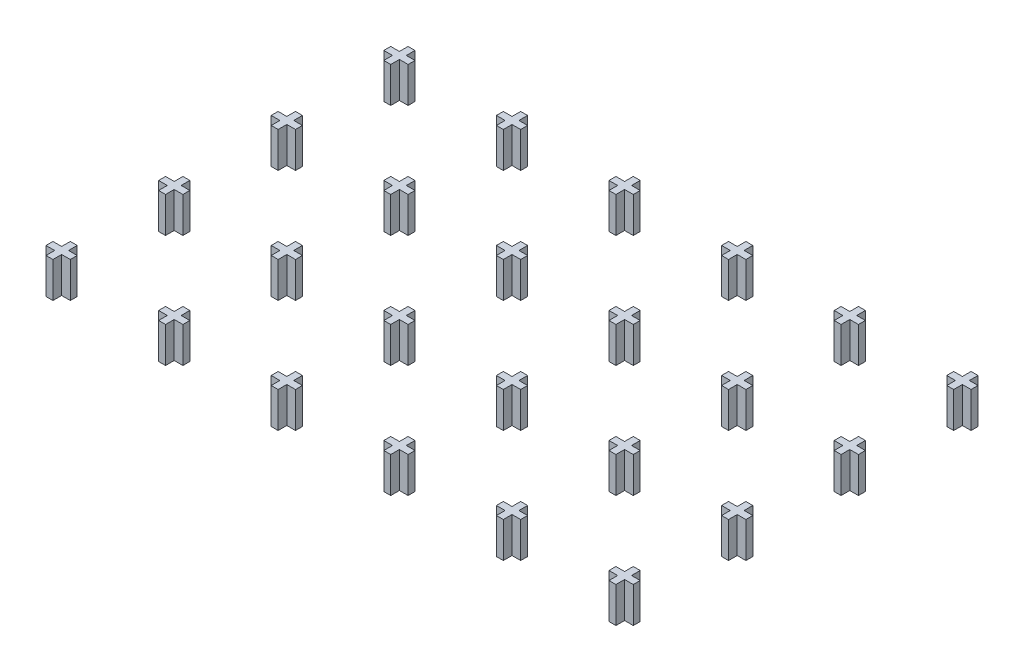
SolidWorks part; units mm, degrees
ref_plane "Front Plane" through (0, 0, 0) normal (0, 0, 1) x (1, 0, 0)
ref_plane "Top Plane" through (0, 0, 0) normal (0, 1, 0) x (1, 0, 0)
ref_plane "Right Plane" through (0, 0, 0) normal (1, 0, 0) x (0, 0, -1)
sketch "Sketch1" plane through (0, 0, 0) normal (0, 1, 0) x (1, 0, 0)
  line L0 (-32.7876, 10.5773) -> (-51.7876, 10.5773) construction
  line L1 (-51.7876, 10.5773) -> (-70.7876, 10.5773) construction
  line L2 (-51.7876, 10.5773) -> (-51.7876, 29.5773) construction
  line L3 (-51.7876, 29.5773) -> (-70.7876, 29.5773) construction
  line L4 (-70.7876, 10.5773) -> (-70.7876, 29.5773) construction
  line L5 (-51.7876, 10.5773) -> (-70.7876, 29.5773) construction
  line L6 (-51.7876, 29.5773) -> (-70.7876, 10.5773) construction
  line L7 (-32.7876, 10.5773) -> (-32.7876, 29.5773) construction
  line L8 (-32.7876, 29.5773) -> (-51.7876, 29.5773) construction
  line L9 (-51.7876, 10.5773) -> (-51.7876, 29.5773) construction
  line L10 (-32.7876, 10.5773) -> (-51.7876, 29.5773) construction
  line L11 (-32.7876, 29.5773) -> (-51.7876, 10.5773) construction
  line L12 (-13.7876, 10.5773) -> (-32.7876, 10.5773) construction
  line L13 (-13.7876, 10.5773) -> (-13.7876, 29.5773) construction
  line L14 (-13.7876, 29.5773) -> (-32.7876, 29.5773) construction
  line L15 (-32.7876, 10.5773) -> (-32.7876, 29.5773) construction
  line L16 (-13.7876, 10.5773) -> (-32.7876, 29.5773) construction
  line L17 (-13.7876, 29.5773) -> (-32.7876, 10.5773) construction
  line L18 (-32.7876, -8.4227) -> (-51.7876, -8.4227) construction
  line L19 (-51.7876, -8.4227) -> (-70.7876, -8.4227) construction
  line L20 (-51.7876, -8.4227) -> (-51.7876, 10.5773) construction
  line L21 (-51.7876, 10.5773) -> (-70.7876, 10.5773) construction
  line L22 (-70.7876, -8.4227) -> (-70.7876, 10.5773) construction
  line L23 (-51.7876, -8.4227) -> (-70.7876, 10.5773) construction
  line L24 (-51.7876, 10.5773) -> (-70.7876, -8.4227) construction
  line L25 (-32.7876, -8.4227) -> (-32.7876, 10.5773) construction
  line L26 (-32.7876, 10.5773) -> (-51.7876, 10.5773) construction
  line L27 (-51.7876, -8.4227) -> (-51.7876, 10.5773) construction
  line L28 (-32.7876, -8.4227) -> (-51.7876, 10.5773) construction
  line L29 (-32.7876, 10.5773) -> (-51.7876, -8.4227) construction
  line L30 (-13.7876, -8.4227) -> (-32.7876, -8.4227) construction
  line L31 (-13.7876, -8.4227) -> (-13.7876, 10.5773) construction
  line L32 (-13.7876, 10.5773) -> (-32.7876, 10.5773) construction
  line L33 (-32.7876, -8.4227) -> (-32.7876, 10.5773) construction
  line L34 (-13.7876, -8.4227) -> (-32.7876, 10.5773) construction
  line L35 (-13.7876, 10.5773) -> (-32.7876, -8.4227) construction
  line L36 (-32.7876, -27.4227) -> (-51.7876, -27.4227) construction
  line L37 (-51.7876, -27.4227) -> (-70.7876, -27.4227) construction
  line L38 (-51.7876, -27.4227) -> (-51.7876, -8.4227) construction
  line L39 (-51.7876, -8.4227) -> (-70.7876, -8.4227) construction
  line L40 (-70.7876, -27.4227) -> (-70.7876, -8.4227) construction
  line L41 (-51.7876, -27.4227) -> (-70.7876, -8.4227) construction
  line L42 (-51.7876, -8.4227) -> (-70.7876, -27.4227) construction
  line L43 (-32.7876, -27.4227) -> (-32.7876, -8.4227) construction
  line L44 (-32.7876, -8.4227) -> (-51.7876, -8.4227) construction
  line L45 (-51.7876, -27.4227) -> (-51.7876, -8.4227) construction
  line L46 (-32.7876, -27.4227) -> (-51.7876, -8.4227) construction
  line L47 (-32.7876, -8.4227) -> (-51.7876, -27.4227) construction
  line L48 (-13.7876, -27.4227) -> (-32.7876, -27.4227) construction
  line L49 (-13.7876, -27.4227) -> (-13.7876, -8.4227) construction
  line L50 (-13.7876, -8.4227) -> (-32.7876, -8.4227) construction
  line L51 (-32.7876, -27.4227) -> (-32.7876, -8.4227) construction
  line L52 (-13.7876, -27.4227) -> (-32.7876, -8.4227) construction
  line L53 (-13.7876, -8.4227) -> (-32.7876, -27.4227) construction
  line L54 (24.2124, 10.5773) -> (5.2124, 10.5773) construction
  line L55 (5.2124, 10.5773) -> (-13.7876, 10.5773) construction
  line L56 (5.2124, 10.5773) -> (5.2124, 29.5773) construction
  line L57 (5.2124, 29.5773) -> (-13.7876, 29.5773) construction
  line L58 (-13.7876, 10.5773) -> (-13.7876, 29.5773) construction
  line L59 (5.2124, 10.5773) -> (-13.7876, 29.5773) construction
  line L60 (5.2124, 29.5773) -> (-13.7876, 10.5773) construction
  line L61 (24.2124, 10.5773) -> (24.2124, 29.5773) construction
  line L62 (24.2124, 29.5773) -> (5.2124, 29.5773) construction
  line L63 (5.2124, 10.5773) -> (5.2124, 29.5773) construction
  line L64 (24.2124, 10.5773) -> (5.2124, 29.5773) construction
  line L65 (24.2124, 29.5773) -> (5.2124, 10.5773) construction
  line L66 (43.2124, 10.5773) -> (24.2124, 10.5773) construction
  line L67 (43.2124, 10.5773) -> (43.2124, 29.5773) construction
  line L68 (43.2124, 29.5773) -> (24.2124, 29.5773) construction
  line L69 (24.2124, 10.5773) -> (24.2124, 29.5773) construction
  line L70 (43.2124, 10.5773) -> (24.2124, 29.5773) construction
  line L71 (43.2124, 29.5773) -> (24.2124, 10.5773) construction
  line L72 (24.2124, -8.4227) -> (5.2124, -8.4227) construction
  line L73 (5.2124, -8.4227) -> (-13.7876, -8.4227) construction
  line L74 (5.2124, -8.4227) -> (5.2124, 10.5773) construction
  line L75 (5.2124, 10.5773) -> (-13.7876, 10.5773) construction
  line L76 (-13.7876, -8.4227) -> (-13.7876, 10.5773) construction
  line L77 (5.2124, -8.4227) -> (-13.7876, 10.5773) construction
  line L78 (5.2124, 10.5773) -> (-13.7876, -8.4227) construction
  line L79 (24.2124, -8.4227) -> (24.2124, 10.5773) construction
  line L80 (24.2124, 10.5773) -> (5.2124, 10.5773) construction
  line L81 (5.2124, -8.4227) -> (5.2124, 10.5773) construction
  line L82 (24.2124, -8.4227) -> (5.2124, 10.5773) construction
  line L83 (24.2124, 10.5773) -> (5.2124, -8.4227) construction
  line L84 (43.2124, -8.4227) -> (24.2124, -8.4227) construction
  line L85 (43.2124, -8.4227) -> (43.2124, 10.5773) construction
  line L86 (43.2124, 10.5773) -> (24.2124, 10.5773) construction
  line L87 (24.2124, -8.4227) -> (24.2124, 10.5773) construction
  line L88 (43.2124, -8.4227) -> (24.2124, 10.5773) construction
  line L89 (43.2124, 10.5773) -> (24.2124, -8.4227) construction
  line L90 (24.2124, -27.4227) -> (5.2124, -27.4227) construction
  line L91 (5.2124, -27.4227) -> (-13.7876, -27.4227) construction
  line L92 (5.2124, -27.4227) -> (5.2124, -8.4227) construction
  line L93 (5.2124, -8.4227) -> (-13.7876, -8.4227) construction
  line L94 (-13.7876, -27.4227) -> (-13.7876, -8.4227) construction
  line L95 (5.2124, -27.4227) -> (-13.7876, -8.4227) construction
  line L96 (5.2124, -8.4227) -> (-13.7876, -27.4227) construction
  line L97 (24.2124, -27.4227) -> (24.2124, -8.4227) construction
  line L98 (24.2124, -8.4227) -> (5.2124, -8.4227) construction
  line L99 (5.2124, -27.4227) -> (5.2124, -8.4227) construction
  line L100 (24.2124, -27.4227) -> (5.2124, -8.4227) construction
  line L101 (24.2124, -8.4227) -> (5.2124, -27.4227) construction
  line L102 (43.2124, -27.4227) -> (24.2124, -27.4227) construction
  line L103 (43.2124, -27.4227) -> (43.2124, -8.4227) construction
  line L104 (43.2124, -8.4227) -> (24.2124, -8.4227) construction
  line L105 (24.2124, -27.4227) -> (24.2124, -8.4227) construction
  line L106 (43.2124, -27.4227) -> (24.2124, -8.4227) construction
  line L107 (43.2124, -8.4227) -> (24.2124, -27.4227) construction
  line L108 (-61.8726, 22.1273) -> (-60.7026, 22.1273)
  line L109 (-60.7026, 22.1273) -> (-60.7026, 20.6623)
  line L110 (-60.7026, 20.6623) -> (-59.2376, 20.6623)
  line L111 (-59.2376, 20.6623) -> (-59.2376, 19.4923)
  line L112 (-59.2376, 19.4923) -> (-60.7026, 19.4923)
  line L113 (-60.7026, 19.4923) -> (-60.7026, 18.0273)
  line L114 (-60.7026, 18.0273) -> (-61.8726, 18.0273)
  line L115 (-61.8726, 18.0273) -> (-61.8726, 19.4923)
  line L116 (-61.8726, 19.4923) -> (-63.3376, 19.4923)
  line L117 (-63.3376, 19.4923) -> (-63.3376, 20.6623)
  line L118 (-63.3376, 20.6623) -> (-61.8726, 20.6623)
  line L119 (-61.8726, 20.6623) -> (-61.8726, 22.1273)
  line L120 (-61.8726, 20.6623) -> (-60.7026, 19.4923) construction
  line L121 (-61.8726, 19.4923) -> (-60.7026, 20.6623) construction
  line L122 (-61.8726, 3.1273) -> (-60.7026, 3.1273)
  line L123 (-60.7026, 3.1273) -> (-60.7026, 1.6623)
  line L124 (-60.7026, 1.6623) -> (-59.2376, 1.6623)
  line L125 (-59.2376, 1.6623) -> (-59.2376, 0.4923)
  line L126 (-59.2376, 0.4923) -> (-60.7026, 0.4923)
  line L127 (-60.7026, 0.4923) -> (-60.7026, -0.9727)
  line L128 (-60.7026, -0.9727) -> (-61.8726, -0.9727)
  line L129 (-61.8726, -0.9727) -> (-61.8726, 0.4923)
  line L130 (-61.8726, 0.4923) -> (-63.3376, 0.4923)
  line L131 (-63.3376, 0.4923) -> (-63.3376, 1.6623)
  line L132 (-63.3376, 1.6623) -> (-61.8726, 1.6623)
  line L133 (-61.8726, 1.6623) -> (-61.8726, 3.1273)
  line L134 (-61.8726, 1.6623) -> (-60.7026, 0.4923) construction
  line L135 (-61.8726, 0.4923) -> (-60.7026, 1.6623) construction
  line L136 (-61.8726, -15.8727) -> (-60.7026, -15.8727)
  line L137 (-60.7026, -15.8727) -> (-60.7026, -17.3377)
  line L138 (-60.7026, -17.3377) -> (-59.2376, -17.3377)
  line L139 (-59.2376, -17.3377) -> (-59.2376, -18.5077)
  line L140 (-59.2376, -18.5077) -> (-60.7026, -18.5077)
  line L141 (-60.7026, -18.5077) -> (-60.7026, -19.9727)
  line L142 (-60.7026, -19.9727) -> (-61.8726, -19.9727)
  line L143 (-61.8726, -19.9727) -> (-61.8726, -18.5077)
  line L144 (-61.8726, -18.5077) -> (-63.3376, -18.5077)
  line L145 (-63.3376, -18.5077) -> (-63.3376, -17.3377)
  line L146 (-63.3376, -17.3377) -> (-61.8726, -17.3377)
  line L147 (-61.8726, -17.3377) -> (-61.8726, -15.8727)
  line L148 (-61.8726, -17.3377) -> (-60.7026, -18.5077) construction
  line L149 (-61.8726, -18.5077) -> (-60.7026, -17.3377) construction
  line L150 (-42.8726, -15.8727) -> (-41.7026, -15.8727)
  line L151 (-41.7026, -15.8727) -> (-41.7026, -17.3377)
  line L152 (-41.7026, -17.3377) -> (-40.2376, -17.3377)
  line L153 (-40.2376, -17.3377) -> (-40.2376, -18.5077)
  line L154 (-40.2376, -18.5077) -> (-41.7026, -18.5077)
  line L155 (-41.7026, -18.5077) -> (-41.7026, -19.9727)
  line L156 (-41.7026, -19.9727) -> (-42.8726, -19.9727)
  line L157 (-42.8726, -19.9727) -> (-42.8726, -18.5077)
  line L158 (-42.8726, -18.5077) -> (-44.3376, -18.5077)
  line L159 (-44.3376, -18.5077) -> (-44.3376, -17.3377)
  line L160 (-44.3376, -17.3377) -> (-42.8726, -17.3377)
  line L161 (-42.8726, -17.3377) -> (-42.8726, -15.8727)
  line L162 (-42.8726, -17.3377) -> (-41.7026, -18.5077) construction
  line L163 (-42.8726, -18.5077) -> (-41.7026, -17.3377) construction
  line L164 (-42.8726, 3.1273) -> (-41.7026, 3.1273)
  line L165 (-41.7026, 3.1273) -> (-41.7026, 1.6623)
  line L166 (-41.7026, 1.6623) -> (-40.2376, 1.6623)
  line L167 (-40.2376, 1.6623) -> (-40.2376, 0.4923)
  line L168 (-40.2376, 0.4923) -> (-41.7026, 0.4923)
  line L169 (-41.7026, 0.4923) -> (-41.7026, -0.9727)
  line L170 (-41.7026, -0.9727) -> (-42.8726, -0.9727)
  line L171 (-42.8726, -0.9727) -> (-42.8726, 0.4923)
  line L172 (-42.8726, 0.4923) -> (-44.3376, 0.4923)
  line L173 (-44.3376, 0.4923) -> (-44.3376, 1.6623)
  line L174 (-44.3376, 1.6623) -> (-42.8726, 1.6623)
  line L175 (-42.8726, 1.6623) -> (-42.8726, 3.1273)
  line L176 (-42.8726, 1.6623) -> (-41.7026, 0.4923) construction
  line L177 (-42.8726, 0.4923) -> (-41.7026, 1.6623) construction
  line L178 (-42.8726, 22.1273) -> (-41.7026, 22.1273)
  line L179 (-41.7026, 22.1273) -> (-41.7026, 20.6623)
  line L180 (-41.7026, 20.6623) -> (-40.2376, 20.6623)
  line L181 (-40.2376, 20.6623) -> (-40.2376, 19.4923)
  line L182 (-40.2376, 19.4923) -> (-41.7026, 19.4923)
  line L183 (-41.7026, 19.4923) -> (-41.7026, 18.0273)
  line L184 (-41.7026, 18.0273) -> (-42.8726, 18.0273)
  line L185 (-42.8726, 18.0273) -> (-42.8726, 19.4923)
  line L186 (-42.8726, 19.4923) -> (-44.3376, 19.4923)
  line L187 (-44.3376, 19.4923) -> (-44.3376, 20.6623)
  line L188 (-44.3376, 20.6623) -> (-42.8726, 20.6623)
  line L189 (-42.8726, 20.6623) -> (-42.8726, 22.1273)
  line L190 (-42.8726, 20.6623) -> (-41.7026, 19.4923) construction
  line L191 (-42.8726, 19.4923) -> (-41.7026, 20.6623) construction
  line L192 (-23.8726, 22.1273) -> (-22.7026, 22.1273)
  line L193 (-22.7026, 22.1273) -> (-22.7026, 20.6623)
  line L194 (-22.7026, 20.6623) -> (-21.2376, 20.6623)
  line L195 (-21.2376, 20.6623) -> (-21.2376, 19.4923)
  line L196 (-21.2376, 19.4923) -> (-22.7026, 19.4923)
  line L197 (-22.7026, 19.4923) -> (-22.7026, 18.0273)
  line L198 (-22.7026, 18.0273) -> (-23.8726, 18.0273)
  line L199 (-23.8726, 18.0273) -> (-23.8726, 19.4923)
  line L200 (-23.8726, 19.4923) -> (-25.3376, 19.4923)
  line L201 (-25.3376, 19.4923) -> (-25.3376, 20.6623)
  line L202 (-25.3376, 20.6623) -> (-23.8726, 20.6623)
  line L203 (-23.8726, 20.6623) -> (-23.8726, 22.1273)
  line L204 (-23.8726, 20.6623) -> (-22.7026, 19.4923) construction
  line L205 (-23.8726, 19.4923) -> (-22.7026, 20.6623) construction
  line L206 (-23.8726, 3.1273) -> (-22.7026, 3.1273)
  line L207 (-22.7026, 3.1273) -> (-22.7026, 1.6623)
  line L208 (-22.7026, 1.6623) -> (-21.2376, 1.6623)
  line L209 (-21.2376, 1.6623) -> (-21.2376, 0.4923)
  line L210 (-21.2376, 0.4923) -> (-22.7026, 0.4923)
  line L211 (-22.7026, 0.4923) -> (-22.7026, -0.9727)
  line L212 (-22.7026, -0.9727) -> (-23.8726, -0.9727)
  line L213 (-23.8726, -0.9727) -> (-23.8726, 0.4923)
  line L214 (-23.8726, 0.4923) -> (-25.3376, 0.4923)
  line L215 (-25.3376, 0.4923) -> (-25.3376, 1.6623)
  line L216 (-25.3376, 1.6623) -> (-23.8726, 1.6623)
  line L217 (-23.8726, 1.6623) -> (-23.8726, 3.1273)
  line L218 (-23.8726, 1.6623) -> (-22.7026, 0.4923) construction
  line L219 (-23.8726, 0.4923) -> (-22.7026, 1.6623) construction
  line L220 (-23.8726, -15.8727) -> (-22.7026, -15.8727)
  line L221 (-22.7026, -15.8727) -> (-22.7026, -17.3377)
  line L222 (-22.7026, -17.3377) -> (-21.2376, -17.3377)
  line L223 (-21.2376, -17.3377) -> (-21.2376, -18.5077)
  line L224 (-21.2376, -18.5077) -> (-22.7026, -18.5077)
  line L225 (-22.7026, -18.5077) -> (-22.7026, -19.9727)
  line L226 (-22.7026, -19.9727) -> (-23.8726, -19.9727)
  line L227 (-23.8726, -19.9727) -> (-23.8726, -18.5077)
  line L228 (-23.8726, -18.5077) -> (-25.3376, -18.5077)
  line L229 (-25.3376, -18.5077) -> (-25.3376, -17.3377)
  line L230 (-25.3376, -17.3377) -> (-23.8726, -17.3377)
  line L231 (-23.8726, -17.3377) -> (-23.8726, -15.8727)
  line L232 (-23.8726, -17.3377) -> (-22.7026, -18.5077) construction
  line L233 (-23.8726, -18.5077) -> (-22.7026, -17.3377) construction
  line L234 (-4.8726, -15.8727) -> (-3.7026, -15.8727)
  line L235 (-3.7026, -15.8727) -> (-3.7026, -17.3377)
  line L236 (-3.7026, -17.3377) -> (-2.2376, -17.3377)
  line L237 (-2.2376, -17.3377) -> (-2.2376, -18.5077)
  line L238 (-2.2376, -18.5077) -> (-3.7026, -18.5077)
  line L239 (-3.7026, -18.5077) -> (-3.7026, -19.9727)
  line L240 (-3.7026, -19.9727) -> (-4.8726, -19.9727)
  line L241 (-4.8726, -19.9727) -> (-4.8726, -18.5077)
  line L242 (-4.8726, -18.5077) -> (-6.3376, -18.5077)
  line L243 (-6.3376, -18.5077) -> (-6.3376, -17.3377)
  line L244 (-6.3376, -17.3377) -> (-4.8726, -17.3377)
  line L245 (-4.8726, -17.3377) -> (-4.8726, -15.8727)
  line L246 (-4.8726, -17.3377) -> (-3.7026, -18.5077) construction
  line L247 (-4.8726, -18.5077) -> (-3.7026, -17.3377) construction
  line L248 (-4.8726, 3.1273) -> (-3.7026, 3.1273)
  line L249 (-3.7026, 3.1273) -> (-3.7026, 1.6623)
  line L250 (-3.7026, 1.6623) -> (-2.2376, 1.6623)
  line L251 (-2.2376, 1.6623) -> (-2.2376, 0.4923)
  line L252 (-2.2376, 0.4923) -> (-3.7026, 0.4923)
  line L253 (-3.7026, 0.4923) -> (-3.7026, -0.9727)
  line L254 (-3.7026, -0.9727) -> (-4.8726, -0.9727)
  line L255 (-4.8726, -0.9727) -> (-4.8726, 0.4923)
  line L256 (-4.8726, 0.4923) -> (-6.3376, 0.4923)
  line L257 (-6.3376, 0.4923) -> (-6.3376, 1.6623)
  line L258 (-6.3376, 1.6623) -> (-4.8726, 1.6623)
  line L259 (-4.8726, 1.6623) -> (-4.8726, 3.1273)
  line L260 (-4.8726, 1.6623) -> (-3.7026, 0.4923) construction
  line L261 (-4.8726, 0.4923) -> (-3.7026, 1.6623) construction
  line L262 (-4.8726, 22.1273) -> (-3.7026, 22.1273)
  line L263 (-3.7026, 22.1273) -> (-3.7026, 20.6623)
  line L264 (-3.7026, 20.6623) -> (-2.2376, 20.6623)
  line L265 (-2.2376, 20.6623) -> (-2.2376, 19.4923)
  line L266 (-2.2376, 19.4923) -> (-3.7026, 19.4923)
  line L267 (-3.7026, 19.4923) -> (-3.7026, 18.0273)
  line L268 (-3.7026, 18.0273) -> (-4.8726, 18.0273)
  line L269 (-4.8726, 18.0273) -> (-4.8726, 19.4923)
  line L270 (-4.8726, 19.4923) -> (-6.3376, 19.4923)
  line L271 (-6.3376, 19.4923) -> (-6.3376, 20.6623)
  line L272 (-6.3376, 20.6623) -> (-4.8726, 20.6623)
  line L273 (-4.8726, 20.6623) -> (-4.8726, 22.1273)
  line L274 (-4.8726, 20.6623) -> (-3.7026, 19.4923) construction
  line L275 (-4.8726, 19.4923) -> (-3.7026, 20.6623) construction
  line L276 (14.1274, 22.1273) -> (15.2974, 22.1273)
  line L277 (15.2974, 22.1273) -> (15.2974, 20.6623)
  line L278 (15.2974, 20.6623) -> (16.7624, 20.6623)
  line L279 (16.7624, 20.6623) -> (16.7624, 19.4923)
  line L280 (16.7624, 19.4923) -> (15.2974, 19.4923)
  line L281 (15.2974, 19.4923) -> (15.2974, 18.0273)
  line L282 (15.2974, 18.0273) -> (14.1274, 18.0273)
  line L283 (14.1274, 18.0273) -> (14.1274, 19.4923)
  line L284 (14.1274, 19.4923) -> (12.6624, 19.4923)
  line L285 (12.6624, 19.4923) -> (12.6624, 20.6623)
  line L286 (12.6624, 20.6623) -> (14.1274, 20.6623)
  line L287 (14.1274, 20.6623) -> (14.1274, 22.1273)
  line L288 (14.1274, 20.6623) -> (15.2974, 19.4923) construction
  line L289 (14.1274, 19.4923) -> (15.2974, 20.6623) construction
  line L290 (14.1274, 3.1273) -> (15.2974, 3.1273)
  line L291 (15.2974, 3.1273) -> (15.2974, 1.6623)
  line L292 (15.2974, 1.6623) -> (16.7624, 1.6623)
  line L293 (16.7624, 1.6623) -> (16.7624, 0.4923)
  line L294 (16.7624, 0.4923) -> (15.2974, 0.4923)
  line L295 (15.2974, 0.4923) -> (15.2974, -0.9727)
  line L296 (15.2974, -0.9727) -> (14.1274, -0.9727)
  line L297 (14.1274, -0.9727) -> (14.1274, 0.4923)
  line L298 (14.1274, 0.4923) -> (12.6624, 0.4923)
  line L299 (12.6624, 0.4923) -> (12.6624, 1.6623)
  line L300 (12.6624, 1.6623) -> (14.1274, 1.6623)
  line L301 (14.1274, 1.6623) -> (14.1274, 3.1273)
  line L302 (14.1274, 1.6623) -> (15.2974, 0.4923) construction
  line L303 (14.1274, 0.4923) -> (15.2974, 1.6623) construction
  line L304 (14.1274, -15.8727) -> (15.2974, -15.8727)
  line L305 (15.2974, -15.8727) -> (15.2974, -17.3377)
  line L306 (15.2974, -17.3377) -> (16.7624, -17.3377)
  line L307 (16.7624, -17.3377) -> (16.7624, -18.5077)
  line L308 (16.7624, -18.5077) -> (15.2974, -18.5077)
  line L309 (15.2974, -18.5077) -> (15.2974, -19.9727)
  line L310 (15.2974, -19.9727) -> (14.1274, -19.9727)
  line L311 (14.1274, -19.9727) -> (14.1274, -18.5077)
  line L312 (14.1274, -18.5077) -> (12.6624, -18.5077)
  line L313 (12.6624, -18.5077) -> (12.6624, -17.3377)
  line L314 (12.6624, -17.3377) -> (14.1274, -17.3377)
  line L315 (14.1274, -17.3377) -> (14.1274, -15.8727)
  line L316 (14.1274, -17.3377) -> (15.2974, -18.5077) construction
  line L317 (14.1274, -18.5077) -> (15.2974, -17.3377) construction
  line L318 (33.1274, -15.8727) -> (34.2974, -15.8727)
  line L319 (34.2974, -15.8727) -> (34.2974, -17.3377)
  line L320 (34.2974, -17.3377) -> (35.7624, -17.3377)
  line L321 (35.7624, -17.3377) -> (35.7624, -18.5077)
  line L322 (35.7624, -18.5077) -> (34.2974, -18.5077)
  line L323 (34.2974, -18.5077) -> (34.2974, -19.9727)
  line L324 (34.2974, -19.9727) -> (33.1274, -19.9727)
  line L325 (33.1274, -19.9727) -> (33.1274, -18.5077)
  line L326 (33.1274, -18.5077) -> (31.6624, -18.5077)
  line L327 (31.6624, -18.5077) -> (31.6624, -17.3377)
  line L328 (31.6624, -17.3377) -> (33.1274, -17.3377)
  line L329 (33.1274, -17.3377) -> (33.1274, -15.8727)
  line L330 (33.1274, -17.3377) -> (34.2974, -18.5077) construction
  line L331 (33.1274, -18.5077) -> (34.2974, -17.3377) construction
  line L332 (33.1274, 3.1273) -> (34.2974, 3.1273)
  line L333 (34.2974, 3.1273) -> (34.2974, 1.6623)
  line L334 (34.2974, 1.6623) -> (35.7624, 1.6623)
  line L335 (35.7624, 1.6623) -> (35.7624, 0.4923)
  line L336 (35.7624, 0.4923) -> (34.2974, 0.4923)
  line L337 (34.2974, 0.4923) -> (34.2974, -0.9727)
  line L338 (34.2974, -0.9727) -> (33.1274, -0.9727)
  line L339 (33.1274, -0.9727) -> (33.1274, 0.4923)
  line L340 (33.1274, 0.4923) -> (31.6624, 0.4923)
  line L341 (31.6624, 0.4923) -> (31.6624, 1.6623)
  line L342 (31.6624, 1.6623) -> (33.1274, 1.6623)
  line L343 (33.1274, 1.6623) -> (33.1274, 3.1273)
  line L344 (33.1274, 1.6623) -> (34.2974, 0.4923) construction
  line L345 (33.1274, 0.4923) -> (34.2974, 1.6623) construction
  line L346 (33.1274, 22.1273) -> (34.2974, 22.1273)
  line L347 (34.2974, 22.1273) -> (34.2974, 20.6623)
  line L348 (34.2974, 20.6623) -> (35.7624, 20.6623)
  line L349 (35.7624, 20.6623) -> (35.7624, 19.4923)
  line L350 (35.7624, 19.4923) -> (34.2974, 19.4923)
  line L351 (34.2974, 19.4923) -> (34.2974, 18.0273)
  line L352 (34.2974, 18.0273) -> (33.1274, 18.0273)
  line L353 (33.1274, 18.0273) -> (33.1274, 19.4923)
  line L354 (33.1274, 19.4923) -> (31.6624, 19.4923)
  line L355 (31.6624, 19.4923) -> (31.6624, 20.6623)
  line L356 (31.6624, 20.6623) -> (33.1274, 20.6623)
  line L357 (33.1274, 20.6623) -> (33.1274, 22.1273)
  line L358 (33.1274, 20.6623) -> (34.2974, 19.4923) construction
  line L359 (33.1274, 19.4923) -> (34.2974, 20.6623) construction
  line L361 (43.2124, -27.4227) -> (43.2124, -46.4227) construction
  line L362 (24.2124, -27.4227) -> (43.2124, -46.4227) construction
  line L363 (-32.7876, -46.4227) -> (-51.7876, -46.4227) construction
  line L364 (-51.7876, -46.4227) -> (-70.7876, -46.4227) construction
  line L365 (-51.7876, -46.4227) -> (-51.7876, -27.4227) construction
  line L366 (-51.7876, -27.4227) -> (-70.7876, -27.4227) construction
  line L367 (-70.7876, -46.4227) -> (-70.7876, -27.4227) construction
  line L368 (-51.7876, -46.4227) -> (-70.7876, -27.4227) construction
  line L369 (-51.7876, -27.4227) -> (-70.7876, -46.4227) construction
  line L370 (-32.7876, -46.4227) -> (-32.7876, -27.4227) construction
  line L371 (-32.7876, -27.4227) -> (-51.7876, -27.4227) construction
  line L372 (-51.7876, -46.4227) -> (-51.7876, -27.4227) construction
  line L373 (-32.7876, -46.4227) -> (-51.7876, -27.4227) construction
  line L374 (-32.7876, -27.4227) -> (-51.7876, -46.4227) construction
  line L375 (-13.7876, -46.4227) -> (-32.7876, -46.4227) construction
  line L376 (-13.7876, -46.4227) -> (-13.7876, -27.4227) construction
  line L377 (-13.7876, -27.4227) -> (-32.7876, -27.4227) construction
  line L378 (-32.7876, -46.4227) -> (-32.7876, -27.4227) construction
  line L379 (-13.7876, -46.4227) -> (-32.7876, -27.4227) construction
  line L380 (-13.7876, -27.4227) -> (-32.7876, -46.4227) construction
  line L381 (24.2124, -46.4227) -> (43.2124, -27.4227) construction
  line L383 (33.1274, -34.8727) -> (34.2974, -34.8727)
  line L384 (24.2124, -46.4227) -> (5.2124, -46.4227) construction
  line L385 (5.2124, -46.4227) -> (-13.7876, -46.4227) construction
  line L386 (5.2124, -46.4227) -> (5.2124, -27.4227) construction
  line L387 (5.2124, -27.4227) -> (-13.7876, -27.4227) construction
  line L388 (-13.7876, -46.4227) -> (-13.7876, -27.4227) construction
  line L389 (5.2124, -46.4227) -> (-13.7876, -27.4227) construction
  line L390 (5.2124, -27.4227) -> (-13.7876, -46.4227) construction
  line L391 (24.2124, -46.4227) -> (24.2124, -27.4227) construction
  line L392 (24.2124, -27.4227) -> (5.2124, -27.4227) construction
  line L393 (5.2124, -46.4227) -> (5.2124, -27.4227) construction
  line L394 (24.2124, -46.4227) -> (5.2124, -27.4227) construction
  line L395 (24.2124, -27.4227) -> (5.2124, -46.4227) construction
  line L396 (43.2124, -46.4227) -> (24.2124, -46.4227) construction
  line L397 (34.2974, -34.8727) -> (34.2974, -36.3377)
  line L398 (43.2124, -27.4227) -> (24.2124, -27.4227) construction
  line L399 (24.2124, -46.4227) -> (24.2124, -27.4227) construction
  line L400 (34.2974, -36.3377) -> (35.7624, -36.3377)
  line L401 (35.7624, -36.3377) -> (35.7624, -37.5077)
  line L402 (-61.8726, -34.8727) -> (-60.7026, -34.8727)
  line L403 (-60.7026, -34.8727) -> (-60.7026, -36.3377)
  line L404 (-60.7026, -36.3377) -> (-59.2376, -36.3377)
  line L405 (-59.2376, -36.3377) -> (-59.2376, -37.5077)
  line L406 (-59.2376, -37.5077) -> (-60.7026, -37.5077)
  line L407 (-60.7026, -37.5077) -> (-60.7026, -38.9727)
  line L408 (-60.7026, -38.9727) -> (-61.8726, -38.9727)
  line L409 (-61.8726, -38.9727) -> (-61.8726, -37.5077)
  line L410 (-61.8726, -37.5077) -> (-63.3376, -37.5077)
  line L411 (-63.3376, -37.5077) -> (-63.3376, -36.3377)
  line L412 (-63.3376, -36.3377) -> (-61.8726, -36.3377)
  line L413 (-61.8726, -36.3377) -> (-61.8726, -34.8727)
  line L414 (-61.8726, -36.3377) -> (-60.7026, -37.5077) construction
  line L415 (-61.8726, -37.5077) -> (-60.7026, -36.3377) construction
  line L416 (-42.8726, -34.8727) -> (-41.7026, -34.8727)
  line L417 (-41.7026, -34.8727) -> (-41.7026, -36.3377)
  line L418 (-41.7026, -36.3377) -> (-40.2376, -36.3377)
  line L419 (-40.2376, -36.3377) -> (-40.2376, -37.5077)
  line L420 (-40.2376, -37.5077) -> (-41.7026, -37.5077)
  line L421 (-41.7026, -37.5077) -> (-41.7026, -38.9727)
  line L422 (-41.7026, -38.9727) -> (-42.8726, -38.9727)
  line L423 (-42.8726, -38.9727) -> (-42.8726, -37.5077)
  line L424 (-42.8726, -37.5077) -> (-44.3376, -37.5077)
  line L425 (-44.3376, -37.5077) -> (-44.3376, -36.3377)
  line L426 (-44.3376, -36.3377) -> (-42.8726, -36.3377)
  line L427 (-42.8726, -36.3377) -> (-42.8726, -34.8727)
  line L428 (-42.8726, -36.3377) -> (-41.7026, -37.5077) construction
  line L429 (-42.8726, -37.5077) -> (-41.7026, -36.3377) construction
  line L430 (-23.8726, -34.8727) -> (-22.7026, -34.8727)
  line L431 (-22.7026, -34.8727) -> (-22.7026, -36.3377)
  line L432 (-22.7026, -36.3377) -> (-21.2376, -36.3377)
  line L433 (-21.2376, -36.3377) -> (-21.2376, -37.5077)
  line L434 (-21.2376, -37.5077) -> (-22.7026, -37.5077)
  line L435 (-22.7026, -37.5077) -> (-22.7026, -38.9727)
  line L436 (-22.7026, -38.9727) -> (-23.8726, -38.9727)
  line L437 (-23.8726, -38.9727) -> (-23.8726, -37.5077)
  line L438 (-23.8726, -37.5077) -> (-25.3376, -37.5077)
  line L439 (-25.3376, -37.5077) -> (-25.3376, -36.3377)
  line L440 (-25.3376, -36.3377) -> (-23.8726, -36.3377)
  line L441 (-23.8726, -36.3377) -> (-23.8726, -34.8727)
  line L442 (-23.8726, -36.3377) -> (-22.7026, -37.5077) construction
  line L443 (-23.8726, -37.5077) -> (-22.7026, -36.3377) construction
  line L444 (-4.8726, -34.8727) -> (-3.7026, -34.8727)
  line L445 (-3.7026, -34.8727) -> (-3.7026, -36.3377)
  line L446 (-3.7026, -36.3377) -> (-2.2376, -36.3377)
  line L447 (-2.2376, -36.3377) -> (-2.2376, -37.5077)
  line L448 (-2.2376, -37.5077) -> (-3.7026, -37.5077)
  line L449 (-3.7026, -37.5077) -> (-3.7026, -38.9727)
  line L450 (-3.7026, -38.9727) -> (-4.8726, -38.9727)
  line L451 (-4.8726, -38.9727) -> (-4.8726, -37.5077)
  line L452 (-4.8726, -37.5077) -> (-6.3376, -37.5077)
  line L453 (-6.3376, -37.5077) -> (-6.3376, -36.3377)
  line L454 (-6.3376, -36.3377) -> (-4.8726, -36.3377)
  line L455 (-4.8726, -36.3377) -> (-4.8726, -34.8727)
  line L456 (-4.8726, -36.3377) -> (-3.7026, -37.5077) construction
  line L457 (-4.8726, -37.5077) -> (-3.7026, -36.3377) construction
  line L458 (14.1274, -34.8727) -> (15.2974, -34.8727)
  line L459 (15.2974, -34.8727) -> (15.2974, -36.3377)
  line L460 (15.2974, -36.3377) -> (16.7624, -36.3377)
  line L461 (16.7624, -36.3377) -> (16.7624, -37.5077)
  line L462 (16.7624, -37.5077) -> (15.2974, -37.5077)
  line L463 (15.2974, -37.5077) -> (15.2974, -38.9727)
  line L464 (15.2974, -38.9727) -> (14.1274, -38.9727)
  line L465 (14.1274, -38.9727) -> (14.1274, -37.5077)
  line L466 (14.1274, -37.5077) -> (12.6624, -37.5077)
  line L467 (12.6624, -37.5077) -> (12.6624, -36.3377)
  line L468 (12.6624, -36.3377) -> (14.1274, -36.3377)
  line L469 (14.1274, -36.3377) -> (14.1274, -34.8727)
  line L470 (14.1274, -36.3377) -> (15.2974, -37.5077) construction
  line L471 (14.1274, -37.5077) -> (15.2974, -36.3377) construction
  line L472 (35.7624, -37.5077) -> (34.2974, -37.5077)
  line L473 (34.2974, -37.5077) -> (34.2974, -38.9727)
  line L474 (34.2974, -38.9727) -> (33.1274, -38.9727)
  line L475 (33.1274, -38.9727) -> (33.1274, -37.5077)
  line L476 (33.1274, -37.5077) -> (31.6624, -37.5077)
  line L477 (31.6624, -37.5077) -> (31.6624, -36.3377)
  line L478 (31.6624, -36.3377) -> (33.1274, -36.3377)
  line L479 (33.1274, -36.3377) -> (33.1274, -34.8727)
  line L480 (33.1274, -36.3377) -> (34.2974, -37.5077) construction
  line L481 (33.1274, -37.5077) -> (34.2974, -36.3377) construction
  point P0 (-61.2876, 20.0773)
  point P6 (-42.2876, 20.0773)
  point P7 (-23.2876, 20.0773)
  point P13 (-61.2876, 1.0773)
  point P18 (-61.2876, -17.9227)
  point P22 (-42.2876, 1.0773)
  point P23 (-23.2876, 1.0773)
  point P31 (-4.2876, 20.0773)
  point P35 (-42.2876, -17.9227)
  point P36 (-23.2876, -17.9227)
  point P44 (-4.2876, 1.0773)
  point P48 (14.7124, 20.0773)
  point P49 (33.7124, 20.0773)
  point P57 (-4.2876, -17.9227)
  point P61 (14.7124, 1.0773)
  point P62 (33.7124, 1.0773)
  point P75 (14.7124, -17.9227)
  point P76 (33.7124, -17.9227)
  point P289 (-61.2876, 20.0773)
  point P290 (-42.2876, 20.0773)
  point P291 (-42.2876, 1.0773)
  point P292 (-61.2876, 1.0773)
  point P293 (-61.2876, -17.9227)
  point P294 (-42.2876, -17.9227)
  point P295 (-23.2876, 20.0773)
  point P296 (-23.2876, 1.0773)
  point P297 (-23.2876, -17.9227)
  point P298 (-4.2876, -17.9227)
  point P299 (-4.2876, 1.0773)
  point P300 (-4.2876, 20.0773)
  point P301 (14.7124, 20.0773)
  point P302 (33.7124, 20.0773)
  point P303 (33.7124, 1.0773)
  point P304 (14.7124, 1.0773)
  point P305 (14.7124, -17.9227)
  point P306 (33.7124, -17.9227)
  point P307 (-61.2876, -36.9227)
  point P310 (33.7124, -36.9227)
  point P313 (33.7124, -36.9227)
  point P317 (-42.2876, -36.9227)
  point P318 (-23.2876, -36.9227)
  point P325 (-4.2876, -36.9227)
  point P335 (14.7124, -36.9227)
  point P336 (33.7124, -36.9227)
  point P409 (33.7124, -36.9227)
  point P415 (-61.2876, -36.9227)
  point P416 (-42.2876, -36.9227)
  point P417 (-23.2876, -36.9227)
  point P418 (-4.2876, -36.9227)
  point P419 (14.7124, -36.9227)
  dimension "D1" = 19
  dimension "D2" = 1.17
  dimension "D3" = 4.1
  dimension "D4" = 1.17
  dimension "D5" = 4.1
  dimension "D6" = 1.17
  dimension "D7" = 4.1
  dimension "D8" = 1.17
  dimension "D9" = 4.1
  dimension "D10" = 1.17
  dimension "D11" = 4.1
  dimension "D12" = 1.17
  dimension "D13" = 4.1
  dimension "D14" = 1.17
  dimension "D15" = 4.1
  dimension "D16" = 1.17
  dimension "D17" = 4.1
  dimension "D18" = 1.17
  dimension "D19" = 4.1
  dimension "D20" = 1.17
  dimension "D21" = 4.1
  dimension "D22" = 1.17
  dimension "D23" = 4.1
  dimension "D24" = 1.17
  dimension "D25" = 4.1
  dimension "D26" = 1.17
  dimension "D27" = 4.1
  dimension "D28" = 1.17
  dimension "D29" = 4.1
  dimension "D30" = 1.17
  dimension "D31" = 4.1
  dimension "D32" = 1.17
  dimension "D33" = 4.1
  dimension "D34" = 1.17
  dimension "D35" = 4.1
  dimension "D36" = 1.17
  dimension "D37" = 4.1
  dimension "D38" = 1.17
  dimension "D39" = 4.1
  dimension "D40" = 1.17
  dimension "D41" = 4.1
  dimension "D42" = 1.17
  dimension "D43" = 4.1
  dimension "D44" = 1.17
  dimension "D45" = 4.1
  dimension "D46" = 1.17
  dimension "D47" = 4.1
  dimension "D48" = 1.17
  dimension "D49" = 4.1
extrude "Boss-Extrude1" add sketch "Sketch1" along normal blind 6
